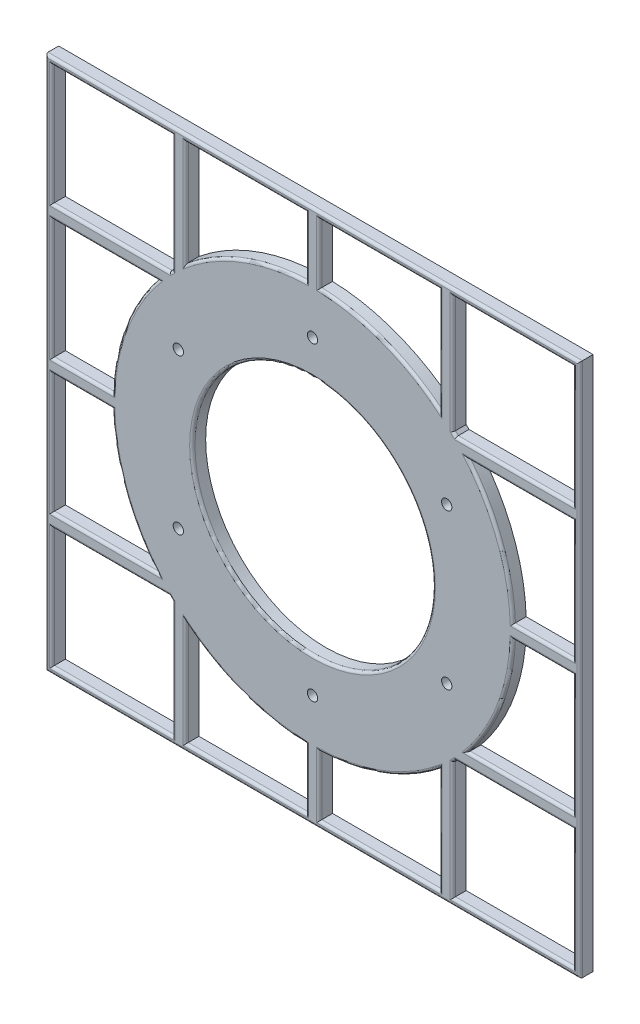
SolidWorks part; units mm, degrees
ref_plane "Front Plane" through (0, 0, 0) normal (0, 0, 1) x (1, 0, 0)
ref_plane "Top Plane" through (0, 0, 0) normal (0, 1, 0) x (1, 0, 0)
ref_plane "Right Plane" through (0, 0, 0) normal (1, 0, 0) x (0, 0, -1)
sketch "Sketch2" plane through (0, 0, 0) normal (0, 0, 1) x (1, 0, 0)
  line L0 (-47.5, -97.5) -> (-2.5, -97.5)
  line L1 (-100, -100) -> (100, -100)
  line L2 (-100, -100) -> (-100, 100)
  line L3 (-100, 100) -> (100, 100)
  line L4 (100, -100) -> (100, 100)
  line L11 (-98.75, -98.75) -> (98.75, 98.75) construction
  line L12 (-98.75, 98.75) -> (98.75, -98.75) construction
  line L13 (-97.5, -97.5) -> (-52.5, -97.5)
  line L14 (-97.5, -97.5) -> (-97.5, -52.5)
  line L15 (-97.5, -52.5) -> (-53.5607, -52.5)
  line L16 (-52.5, -97.5) -> (-52.5, -53.5607)
  line L17 (-97.5, -97.5) -> (-52.5, -52.5) construction
  line L18 (-97.5, -52.5) -> (-52.5, -97.5) construction
  line L19 (-47.5, -97.5) -> (-47.5, -58.0409)
  line L21 (-2.5, -97.5) -> (-2.5, -74.9583)
  line L22 (-47.5, -97.5) -> (-2.5, -52.5) construction
  line L23 (-47.5, -52.5) -> (-2.5, -97.5) construction
  line L24 (2.5, -97.5) -> (47.5, -97.5)
  line L25 (2.5, -97.5) -> (2.5, -74.9583)
  line L27 (47.5, -97.5) -> (47.5, -58.0409)
  line L28 (2.5, -97.5) -> (47.5, -52.5) construction
  line L29 (2.5, -52.5) -> (47.5, -97.5) construction
  line L30 (52.5, -97.5) -> (97.5, -97.5)
  line L31 (52.5, -97.5) -> (52.5, -53.5607)
  line L32 (53.5607, -52.5) -> (97.5, -52.5)
  line L33 (97.5, -97.5) -> (97.5, -52.5)
  line L34 (52.5, -97.5) -> (97.5, -52.5) construction
  line L35 (52.5, -52.5) -> (97.5, -97.5) construction
  line L40 (-47.5, -47.5) -> (-2.5, -2.5) construction
  line L41 (-47.5, -2.5) -> (-2.5, -47.5) construction
  line L46 (2.5, -47.5) -> (47.5, -2.5) construction
  line L47 (2.5, -2.5) -> (47.5, -47.5) construction
  line L48 (58.0409, -47.5) -> (97.5, -47.5)
  line L50 (74.9583, -2.5) -> (97.5, -2.5)
  line L51 (97.5, -47.5) -> (97.5, -2.5)
  line L52 (52.5, -47.5) -> (97.5, -2.5) construction
  line L53 (52.5, -2.5) -> (97.5, -47.5) construction
  line L58 (-47.5, 2.5) -> (-2.5, 47.5) construction
  line L59 (-47.5, 47.5) -> (-2.5, 2.5) construction
  line L64 (2.5, 2.5) -> (47.5, 47.5) construction
  line L65 (2.5, 47.5) -> (47.5, 2.5) construction
  line L66 (74.9583, 2.5) -> (97.5, 2.5)
  line L68 (58.0409, 47.5) -> (97.5, 47.5)
  line L69 (97.5, 2.5) -> (97.5, 47.5)
  line L70 (52.5, 2.5) -> (97.5, 47.5) construction
  line L71 (52.5, 47.5) -> (97.5, 2.5) construction
  line L73 (-47.5, 58.0409) -> (-47.5, 97.5)
  line L74 (-47.5, 97.5) -> (-2.5, 97.5)
  line L75 (-2.5, 74.9583) -> (-2.5, 97.5)
  line L76 (-47.5, 52.5) -> (-2.5, 97.5) construction
  line L77 (-47.5, 97.5) -> (-2.5, 52.5) construction
  line L79 (2.5, 74.9583) -> (2.5, 97.5)
  line L80 (2.5, 97.5) -> (47.5, 97.5)
  line L81 (47.5, 58.0409) -> (47.5, 97.5)
  line L82 (2.5, 52.5) -> (47.5, 97.5) construction
  line L83 (2.5, 97.5) -> (47.5, 52.5) construction
  line L84 (53.5607, 52.5) -> (97.5, 52.5)
  line L85 (52.5, 53.5607) -> (52.5, 97.5)
  line L86 (52.5, 97.5) -> (97.5, 97.5)
  line L87 (97.5, 52.5) -> (97.5, 97.5)
  line L88 (52.5, 52.5) -> (97.5, 97.5) construction
  line L89 (52.5, 97.5) -> (97.5, 52.5) construction
  line L90 (-97.5, -47.5) -> (-58.0409, -47.5)
  line L91 (-97.5, -47.5) -> (-97.5, -2.5)
  line L92 (-97.5, -2.5) -> (-74.9583, -2.5)
  line L94 (-97.5, -47.5) -> (-52.5, -2.5) construction
  line L95 (-97.5, -2.5) -> (-52.5, -47.5) construction
  line L96 (-97.5, 2.5) -> (-74.9583, 2.5)
  line L97 (-97.5, 2.5) -> (-97.5, 47.5)
  line L98 (-97.5, 47.5) -> (-58.0409, 47.5)
  line L100 (-97.5, 2.5) -> (-52.5, 47.5) construction
  line L101 (-97.5, 47.5) -> (-52.5, 2.5) construction
  line L102 (-97.5, 52.5) -> (-53.5607, 52.5)
  line L103 (-97.5, 52.5) -> (-97.5, 97.5)
  line L104 (-97.5, 97.5) -> (-52.5, 97.5)
  line L105 (-52.5, 53.5607) -> (-52.5, 97.5)
  line L106 (-97.5, 52.5) -> (-52.5, 97.5) construction
  line L107 (-97.5, 97.5) -> (-52.5, 52.5) construction
  line L108 (-2.5, -2.5) -> (2.5, 2.5) construction
  line L109 (2.5, -2.5) -> (-2.5, 2.5) construction
  line L110 (-47.5, 2.5) -> (-2.5, 2.5) [skipped]
  line L111 (-47.5, -2.5) -> (-2.5, -2.5) [skipped]
  line L112 (2.5, -2.5) -> (47.5, -2.5) [skipped]
  line L113 (2.5, 2.5) -> (47.5, 2.5) [skipped]
  line L114 (47.5, 2.5) -> (47.5, 47.5) [skipped]
  line L115 (52.5, 2.5) -> (52.5, 47.5) [skipped]
  line L116 (52.5, -47.5) -> (52.5, -2.5) [skipped]
  line L117 (47.5, -47.5) -> (47.5, -2.5) [skipped]
  line L118 (2.5, -47.5) -> (47.5, -47.5) [skipped]
  line L119 (-47.5, -47.5) -> (-2.5, -47.5) [skipped]
  line L120 (-47.5, -47.5) -> (-47.5, -2.5) [skipped]
  line L121 (-52.5, -47.5) -> (-52.5, -2.5) [skipped]
  line L122 (-47.5, 2.5) -> (-47.5, 47.5) [skipped]
  line L123 (-52.5, 2.5) -> (-52.5, 47.5) [skipped]
  line L124 (2.5, -52.5) -> (47.5, -52.5) [skipped]
  line L125 (-47.5, -52.5) -> (-2.5, -52.5) [skipped]
  line L126 (2.5, 47.5) -> (47.5, 47.5) [skipped]
  line L127 (2.5, 2.5) -> (2.5, 47.5) [skipped]
  line L128 (2.5, -47.5) -> (2.5, -2.5) [skipped]
  line L129 (-2.5, -47.5) -> (-2.5, -2.5) [skipped]
  line L130 (-47.5, 47.5) -> (-2.5, 47.5) [skipped]
  line L131 (-47.5, 52.5) -> (-2.5, 52.5) [skipped]
  line L132 (2.5, 52.5) -> (47.5, 52.5) [skipped]
  line L133 (-2.5, 2.5) -> (-2.5, 47.5) [skipped]
  arc A0 (-52.5, 53.5607) -> (-53.5607, 52.5) centre (0, 0) ccw
  arc A1 (-58.0409, 47.5) -> (-74.9583, 2.5) centre (0, 0) ccw
  arc A2 (-2.5, 74.9583) -> (-47.5, 58.0409) centre (0, 0) ccw
  arc A3 (47.5, 58.0409) -> (2.5, 74.9583) centre (0, 0) ccw
  arc A4 (53.5607, 52.5) -> (52.5, 53.5607) centre (0, 0) ccw
  arc A5 (74.9583, 2.5) -> (58.0409, 47.5) centre (0, 0) ccw
  arc A6 (58.0409, -47.5) -> (74.9583, -2.5) centre (0, 0) ccw
  arc A7 (52.5, -53.5607) -> (53.5607, -52.5) centre (0, 0) ccw
  arc A8 (2.5, -74.9583) -> (47.5, -58.0409) centre (0, 0) ccw
  arc A9 (-74.9583, -2.5) -> (-58.0409, -47.5) centre (0, 0) ccw
  arc A10 (-47.5, -58.0409) -> (-2.5, -74.9583) centre (0, 0) ccw
  arc A11 (-53.5607, -52.5) -> (-52.5, -53.5607) centre (0, 0) ccw
  circle A12 centre (0, 0) radius 45
  point P0 (0, 0)
  point P5 (0, 0)
  point P11 (-75, -75)
  point P18 (-25, -75)
  point P23 (25, -75)
  point P28 (75, -75)
  point P33 (-25, -25)
  point P38 (25, -25)
  point P43 (75, -25)
  point P48 (-25, 25)
  point P53 (25, 25)
  point P58 (75, 25)
  point P63 (-25, 75)
  point P68 (25, 75)
  point P73 (75, 75)
  point P78 (-75, -25)
  point P83 (-75, 25)
  point P88 (-75, 75)
  dimension "D1" = 200
  dimension "D2" = 4
  dimension "D3" = 4
  dimension "D4" = 200
extrude "Boss-Extrude1" add sketch "Sketch2" along normal blind 5
fillet "Fillet2" radius 1 57 edges at (-75, 97.5, 5) (-97.5, 75, 5) (-75.5304, 52.5, 5) (-52.5, 75.5304, 5) (-86.2292, -2.5, 5) (-97.5, -25, 5) (-77.7705, -47.5, 5) (25, 97.5, 5) (2.5, 86.2292, 5) (47.5, 77.7705, 5) (77.7705, 47.5, 5) (86.2292, 2.5, 5) (97.5, 25, 5) (75.5304, -52.5, 5) (52.5, -75.5304, 5) (75, -97.5, 5) (97.5, -75, 5) (-47.5, -77.7705, 5) (-25, -97.5, 5) (-2.5, -86.2292, 5) (0, -100, 5) (-100, 0, 5) (0, 100, 5) (100, 0, 5) (-75.5304, -52.5, 5) (-97.5, -75, 5) (-75, -97.5, 5) (-52.5, -75.5304, 5) (2.5, -86.2292, 5) (25, -97.5, 5) (47.5, -77.7705, 5) (86.2292, -2.5, 5) (77.7705, -47.5, 5) (97.5, -25, 5) (-25, 97.5, 5) (-47.5, 77.7705, 5) (-2.5, 86.2292, 5) (75, 97.5, 5) (52.5, 75.5304, 5) (75.5304, 52.5, 5) (97.5, 75, 5) (-77.7705, 47.5, 5) (-97.5, 25, 5) (-86.2292, 2.5, 5) (45, 0, 5) (-53.033, 53.033, 5) (-70.2029, -26.3922, 5) (26.3922, 70.2029, 5) (70.2029, -26.3922, 5) (26.3922, -70.2029, 5) (-26.3922, 70.2029, 5) (-53.033, -53.033, 5) (-26.3922, -70.2029, 5) (53.033, -53.033, 5) (70.2029, 26.3922, 5) (53.033, 53.033, 5) (-70.2029, 26.3922, 5)
sketch "Sketch3" plane through (0, 0, 0) normal (0, 0, 1) x (1, 0, 0)
  line L0 (-77, 0) -> (77, 0) construction
  line L1 (0, 0) -> (0, 58) construction
  circle A1 centre (0, 0) radius 58 construction
  circle A2 centre (0, 58) radius 1.925
  circle A3 centre (50.2295, 29) radius 1.925
  circle A4 centre (50.2295, -29) radius 1.925
  circle A5 centre (0, -58) radius 1.925
  circle A6 centre (-50.2295, -29) radius 1.925
  circle A7 centre (-50.2295, 29) radius 1.925
  dimension "D1" = 6
extrude "Cut-Extrude1" cut sketch "Sketch3" along normal blind 10
